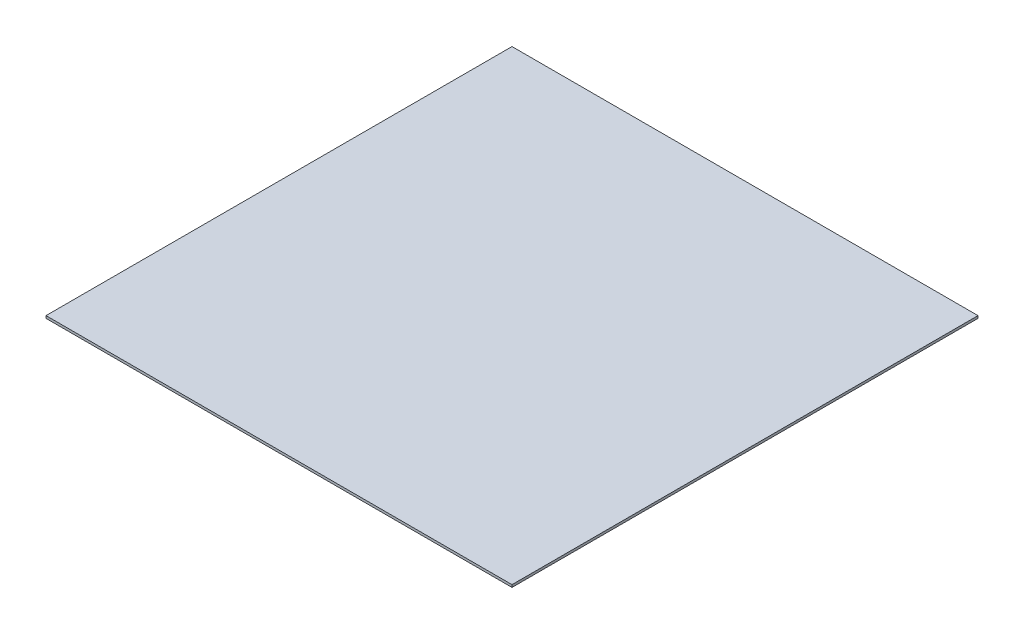
SolidWorks part; units mm, degrees
material "PC High Viscosity"
ref_plane "Front Plane" through (0, 0, 0) normal (0, 0, 1) x (1, 0, 0)
ref_plane "Top Plane" through (0, 0, 0) normal (0, 1, 0) x (1, 0, 0)
ref_plane "Right Plane" through (0, 0, 0) normal (1, 0, 0) x (0, 0, -1)
sketch "Sketch1" plane through (0, 0, 0) normal (0, 1, 0) x (1, 0, 0)
  line L1 (0, 0) -> (1219.2, 0)
  line L2 (0, 0) -> (0, 1219.2)
  line L3 (0, 1219.2) -> (1219.2, 1219.2)
  line L4 (1219.2, 0) -> (1219.2, 1219.2)
  dimension "D1" = 1219.2
  dimension "D2" = 1219.2
extrude "Boss-Extrude1" add sketch "Sketch1" along normal blind 6.35
hole_wizard "1/4 Clearance Hole1" [suppressed] positions "Sketch2" profile "Sketch3" hole size "1/4" standard "ANSI Inch"
sketch "Sketch2" plane through (0, 6.35, 0) normal (0, 1, 0) x (1, 0, 0)
  line L5 (0, 1219.2) -> (0, 0) construction
  line L8 (1219.2, 609.6) -> (0, 609.6) construction
  line L9 (1219.2, 0) -> (1219.2, 1219.2) construction
  point P0 (409.575, 987.425)
  point P23 (409.575, 231.775)
  point P25 (22.225, 914.4)
  point P37 (22.225, 304.8)
  point P51 (1168.4, 304.8)
  point P52 (1168.4, 914.4)
  point P53 (781.05, 231.775)
  point P54 (781.05, 987.425)
  dimension "D1" = 377.825
  dimension "D2" = 409.575
  dimension "D3" = 304.8
  dimension "D4" = 22.225
  dimension "D5" = 781.05
  dimension "D6" = 1168.4
sketch "Sketch3" plane through (409.575, 6.35, -987.425) normal (1, 0, 0) x (0, 0, 1)
  line L0 (0, 0) -> (0, 6.35)
  line L1 (0, 6.35) -> (3.5712, 6.35)
  line L2 (3.5712, 6.35) -> (3.5712, 0)
  line L5 (3.5712, 0) -> (0, 0)
  line L11 (0, -6.35) -> (0, 107.95) construction
  dimension "Thru Hole Dia." = 7.1425
  dimension "Thru Hole Depth" = 6.35
fillet "Fillet1" [suppressed] radius 3.175
